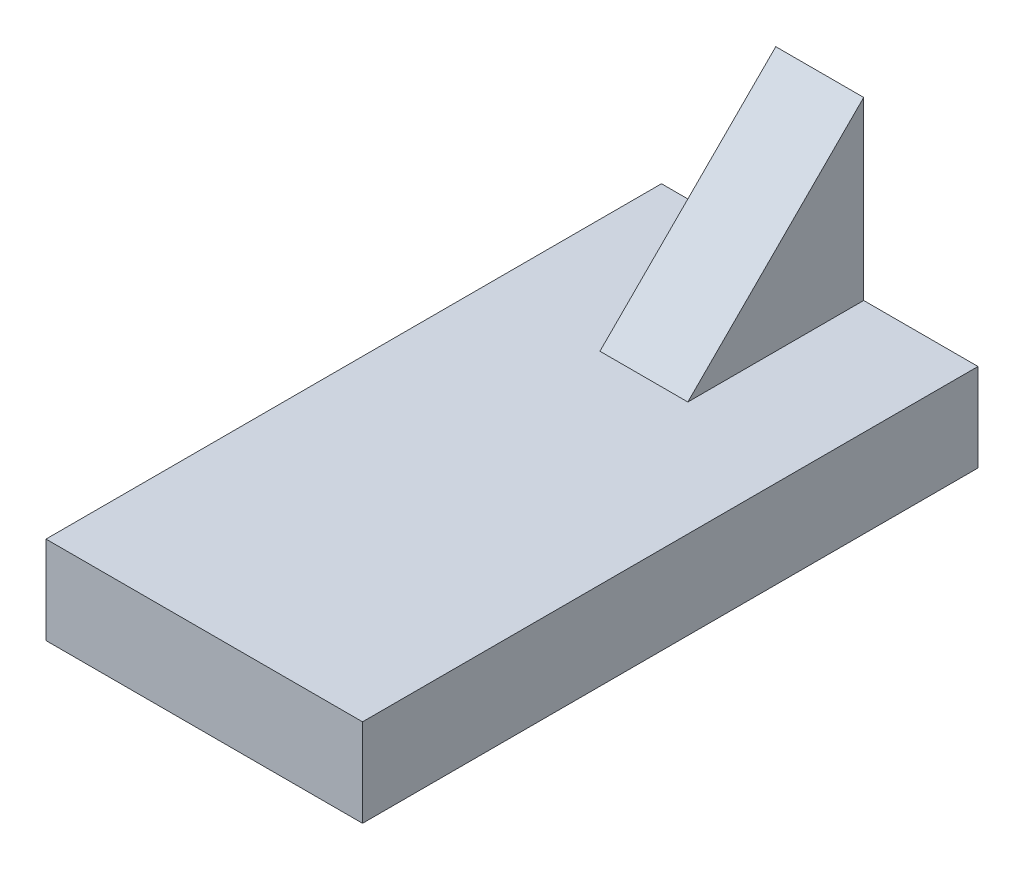
SolidWorks part; units mm, degrees
ref_plane "前视基准面" through (0, 0, 0) normal (0, 0, 1) x (1, 0, 0)
ref_plane "上视基准面" through (0, 0, 0) normal (0, 1, 0) x (1, 0, 0)
ref_plane "右视基准面" through (0, 0, 0) normal (1, 0, 0) x (0, 0, -1)
other "Configuration Table"
sketch "草图1" plane through (0, 0, 1023.1543) normal (0, 0, -1) x (-1, 0, 0)
  line L2 (68.6066, -108.7835) -> (104.6066, -108.7835)
  line L3 (68.6066, -108.7835) -> (68.6066, -98.7835)
  line L4 (68.6066, -98.7835) -> (104.6066, -98.7835)
  line L5 (104.6066, -108.7835) -> (104.6066, -98.7835)
extrude "凸台-拉伸1" add sketch "草图1" along normal blind 70
ref_plane "基准面1" through (-86.6066, 0, 0) normal (-1, 0, 0) x (0, 0, 1)
sketch "草图3" plane through (-86.6066, 0, 0) normal (-1, 0, 0) x (0, 0, 1)
  line L0 (953.1543, -98.7835) -> (953.1543, -78.7835)
  line L1 (953.1543, 11.2165) -> (953.1543, -209.7835) construction
  line L2 (953.1543, -78.7835) -> (973.1543, -98.7835)
  line L3 (953.1543, -98.7835) -> (1023.1543, -98.7835) construction
  line L4 (973.1543, -98.7835) -> (953.1543, -98.7835)
extrude "凸台-拉伸2" add sketch "草图3" along normal blind 5 and the other way blind 5
